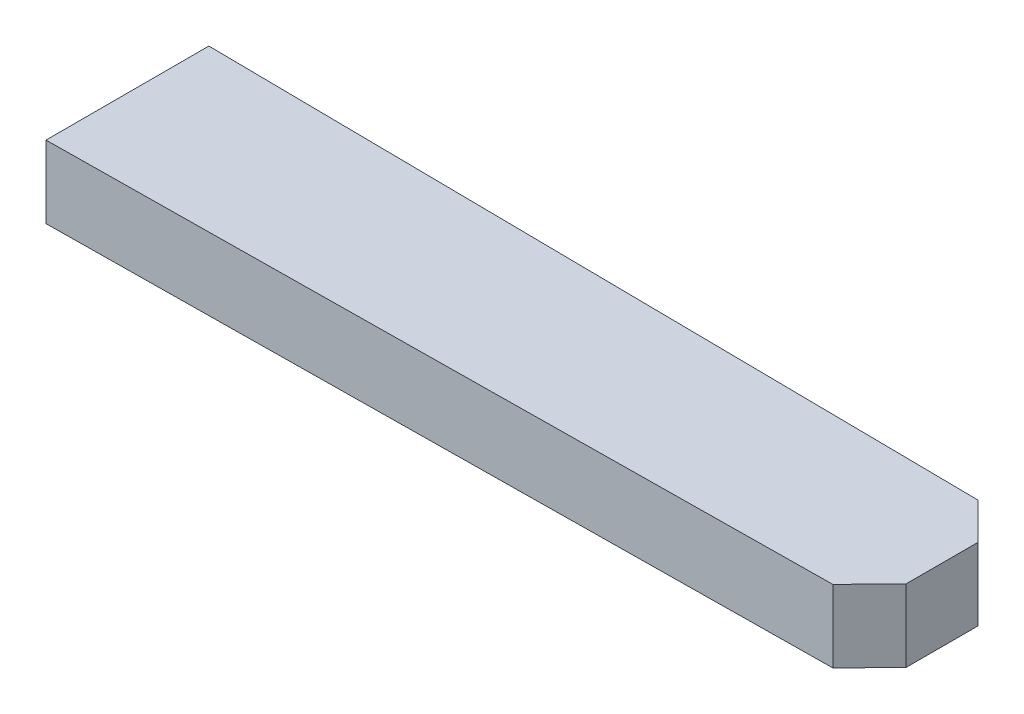
SolidWorks part; units mm, degrees
material "Oak"
ref_plane "Front Plane" through (0, 0, 0) normal (0, 0, 1) x (1, 0, 0)
ref_plane "Top Plane" through (0, 0, 0) normal (0, 1, 0) x (1, 0, 0)
ref_plane "Right Plane" through (0, 0, 0) normal (1, 0, 0) x (0, 0, -1)
sketch "Sketch2" plane through (0, 0, 0) normal (0, 1, 0) x (1, 0, 0)
  line L0 (0, 9) -> (45, 8.5)
  line L1 (0, 0) -> (45, 0) construction
  line L2 (0, 0) -> (0, 9) construction
  line L3 (0, 9) -> (45, 9) construction
  line L4 (45, 0) -> (45, 9) construction
  line L5 (45, 8.5) -> (45, 0.5)
  line L6 (45, 0.5) -> (0, 0)
  line L7 (0, 9) -> (0, 0)
  point P8 (45, 4.5)
  point P9 (45, 4.5)
  dimension "D1" = 45
  dimension "D2" = 9
  dimension "D3" = 8
extrude "Boss-Extrude1" add sketch "Sketch2" along normal blind 4
chamfer "Chamfer2" distance 2 angle 45 2 edges at (45, 2, -0.5) (45, 2, -8.5)
